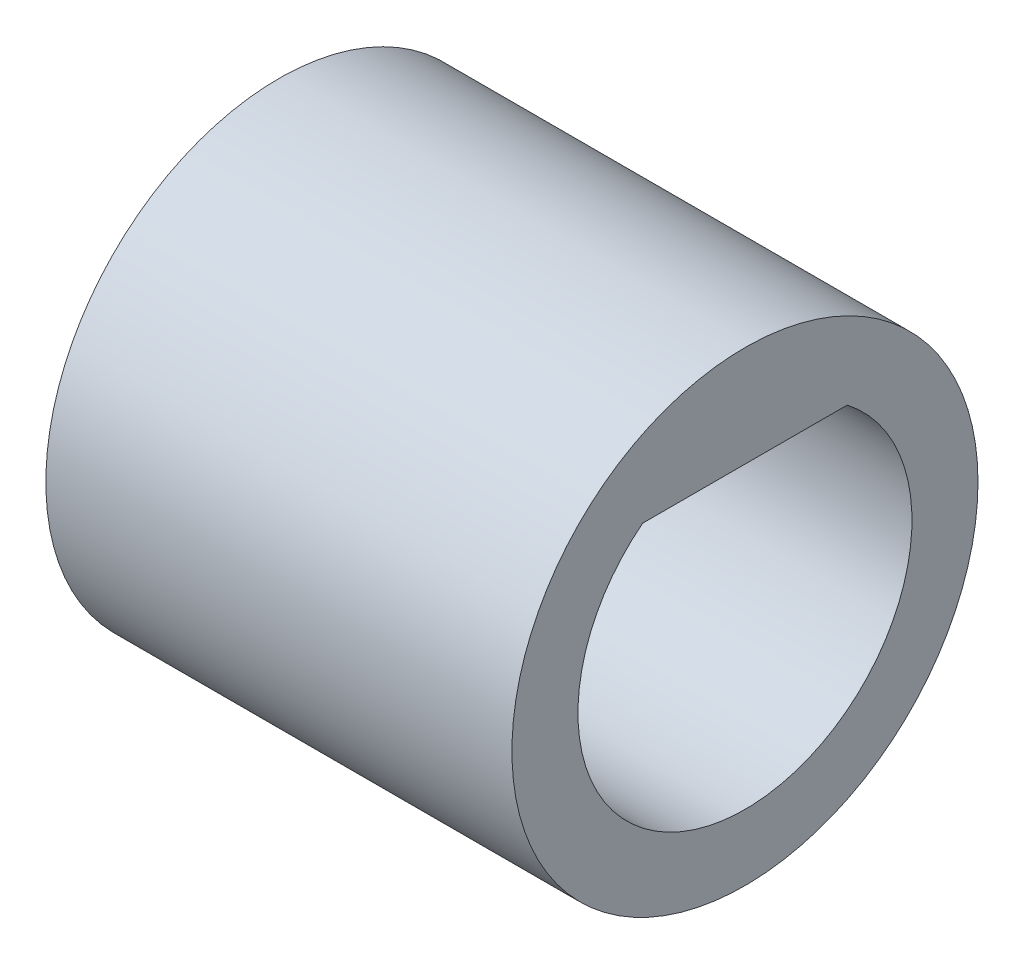
SolidWorks part; units mm, degrees
ref_plane "Front Plane" through (0, 0, 0) normal (0, 0, 1) x (1, 0, 0)
ref_plane "Top Plane" through (0, 0, 0) normal (0, 1, 0) x (1, 0, 0)
ref_plane "Right Plane" through (0, 0, 0) normal (1, 0, 0) x (0, 0, -1)
sketch "Sketch1" plane through (0, 0, 0) normal (1, 0, 0) x (0, 0, -1)
  line L0 (-1.9, 1.8473) -> (-1.9, -1.8473)
  line L1 (1.9, 1.8473) -> (1.9, -1.8473)
  arc A0 (-1.9, -1.8473) -> (1.9, -1.8473) centre (0, 0) ccw
  arc A2 (1.9, 1.8473) -> (-1.9, 1.8473) centre (0, 0) ccw
  dimension "D3" = 5.3
  dimension "D1" = 3.8
  dimension "D2" = 1.9
sketch "Sketch5" plane through (0, 0, 0) normal (1, 0, 0) x (0, 0, -1)
  line L0 (-1.3162, 1.7) -> (1.3162, 1.7) construction
  arc A0 (-1.3162, 1.7) -> (1.3162, 1.7) centre (0, 0) ccw construction
  circle A1 centre (0, 0) radius 3
  dimension "D1" = 4.3
  dimension "D3" = 6
  dimension "D2" = 1.7
extrude "Boss-Extrude2" add sketch "Sketch5" along normal blind 6 contours A1
sketch "Sketch7" plane through (6, 0, 0) normal (1, 0, 0) x (0, 0, -1)
  line L0 (-1.3162, 1.7) -> (1.3162, 1.7)
  arc A0 (-1.3162, 1.7) -> (1.3162, 1.7) centre (0, 0) ccw
  arc A1 (-1.3162, 1.7) -> (1.3162, 1.7) centre (0, 0) ccw construction
extrude "Cut-Extrude1" cut sketch "Sketch7" against normal blind 5
equation "\"D2@Sketch1\"=\"D1@Sketch1\"/2"
